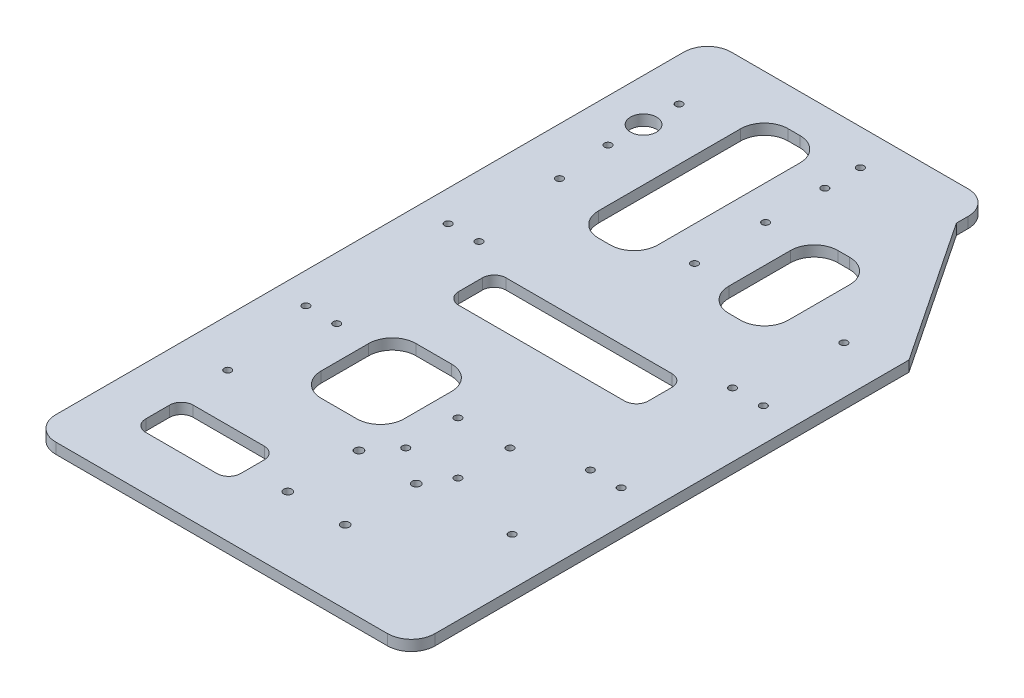
SolidWorks part; units mm, degrees
ref_plane "前视基准面" through (0, 0, 0) normal (0, 0, 1) x (1, 0, 0)
ref_plane "上视基准面" through (0, 0, 0) normal (0, 1, 0) x (1, 0, 0)
ref_plane "右视基准面" through (0, 0, 0) normal (1, 0, 0) x (0, 0, -1)
other "Configuration Table"
sketch "草图1" plane through (0, 0, 0) normal (0, 1, 0) x (1, 0, 0)
  line L1 (-80, 0) -> (80, 0)
  line L6 (0, 0) -> (0, 132.0858) construction
  line L26 (-80, 285) -> (-80, 0)
  line L27 (40, 270) -> (80, 210)
  line L28 (80, 0) -> (80, 210)
  line L29 (-80, 285) -> (40, 285)
  line L30 (40, 285) -> (40, 270)
  point P1 (0, 0)
  dimension "D1" = 160
  dimension "D2" = 285
  dimension "D3" = 120
extrude "凸台-拉伸1" add sketch "草图1" along normal blind 4.5
sketch "草图2" plane through (0, 4.5, 0) normal (0, 1, 0) x (1, 0, 0)
  line L0 (-80, 285) -> (-80, 0) construction
  line L2 (40, 285) -> (-80, 285) construction
  circle A0 centre (-60, 230) radius 6
  dimension "D2" = 12
  dimension "D1" = 20
  dimension "D3" = 55
sketch "草图3" plane through (0, 4.5, 0) normal (0, 1, 0) x (1, 0, 0)
  circle A0 centre (-2.95, 60.8584) radius 1.75
  circle A1 centre (21.25, 60.8584) radius 1.75
  circle A2 centre (21.25, 30.8584) radius 1.75
  circle A3 centre (-2.95, 30.8584) radius 1.75
extrude "切除-拉伸2" cut sketch "草图3" against normal through all
sketch "草图4" plane through (0, 4.5, 0) normal (0, 1, 0) x (1, 0, 0)
  circle A0 centre (-60, 202.5482) radius 1.5
  circle A1 centre (-67, 162.5482) radius 1.5
  circle A2 centre (-54, 162.5482) radius 1.5
  circle A3 centre (-67, 102.5482) radius 1.5
  circle A4 centre (-54, 102.5482) radius 1.5
  circle A5 centre (-60, 62.5482) radius 1.5
  circle A6 centre (60, 62.5482) radius 1.5
  circle A7 centre (53, 102.5482) radius 1.5
  circle A8 centre (66, 102.5482) radius 1.5
  circle A9 centre (53, 162.5482) radius 1.5
  circle A10 centre (66, 162.5482) radius 1.5
  circle A11 centre (60, 202.5482) radius 1.5
  dimension "D1" = 3
  dimension "D2" = 3
extrude "切除-拉伸3" cut sketch "草图4" against normal through all
sketch "草图6" plane through (0, 4.5, 0) normal (0, 1, 0) x (1, 0, 0)
  circle A0 centre (-62, 255) radius 1.5
fillet "圆角1" radius 10 4 edges at (-80, 2.25, -285) (40, 2.25, -285) (80, 2.25, 0) (-80, 2.25, 0)
sketch "草图7" plane through (0, 4.5, 0) normal (0, 1, 0) x (1, 0, 0)
  circle A0 centre (-62, 255) radius 1.5
  circle A1 centre (-62, 225) radius 1.5
extrude "切除-拉伸4" cut sketch "草图7" against normal through all
sketch "草图8" plane through (0, 4.5, 0) normal (0, 1, 0) x (1, 0, 0)
  circle A0 centre (-0.5, 270) radius 1.5
  circle A1 centre (-0.5, 255) radius 1.5
  circle A2 centre (-0.5, 230) radius 1.5
  circle A3 centre (-0.5, 200) radius 1.5
  dimension "D1" = 3
extrude "切除-拉伸5" cut sketch "草图8" against normal through all
sketch "草图9" plane through (0, 4.5, 0) normal (0, 1, 0) x (1, 0, 0)
  line L6 (-80, 275) -> (-80, 10) construction
  line L11 (-30, 269) -> (-25, 269)
  line L14 (-40, 259) -> (-40, 199)
  line L15 (-30, 189) -> (-25, 189)
  line L16 (-15, 259) -> (-15, 199)
  line L17 (30, 285) -> (-70, 285) construction
  line L18 (-70, 0) -> (70, 0) construction
  line L19 (25, 189) -> (30, 189)
  line L20 (15, 199) -> (15, 225)
  line L21 (25, 235) -> (30, 235)
  line L22 (40, 199) -> (40, 225)
  line L23 (-35, 155) -> (35, 155)
  line L24 (-40, 150) -> (-40, 140)
  line L25 (-35, 135) -> (35, 135)
  line L26 (40, 150) -> (40, 140)
  line L27 (-30, 112) -> (-15, 112)
  line L28 (-40, 102) -> (-40, 82)
  line L29 (-30, 72) -> (-15, 72)
  line L31 (-54.5, 22.5) -> (-24.5, 22.5)
  line L32 (-59.5, 27.5) -> (-59.5, 37.5)
  line L33 (-54.5, 42.5) -> (-24.5, 42.5)
  line L34 (-19.5, 27.5) -> (-19.5, 37.5)
  line L35 (-5, 102) -> (-5, 82)
  arc A4 (-40, 82) -> (-30, 72) centre (-30, 82) ccw
  arc A5 (-15, 72) -> (-5, 82) centre (-15, 82) ccw
  arc A6 (-5, 102) -> (-15, 112) centre (-15, 102) ccw
  arc A7 (-40, 102) -> (-30, 112) centre (-30, 102) cw
  arc A8 (40, 225) -> (30, 235) centre (30, 225) ccw
  arc A9 (30, 189) -> (40, 199) centre (30, 199) ccw
  arc A10 (25, 189) -> (15, 199) centre (25, 199) cw
  arc A11 (15, 225) -> (25, 235) centre (25, 225) cw
  arc A12 (-15, 259) -> (-25, 269) centre (-25, 259) ccw
  arc A13 (-25, 189) -> (-15, 199) centre (-25, 199) ccw
  arc A14 (-30, 189) -> (-40, 199) centre (-30, 199) cw
  arc A15 (-40, 259) -> (-30, 269) centre (-30, 259) cw
  arc A16 (-19.5, 27.5) -> (-24.5, 22.5) centre (-24.5, 27.5) cw
  arc A17 (-19.5, 37.5) -> (-24.5, 42.5) centre (-24.5, 37.5) ccw
  arc A18 (-59.5, 27.5) -> (-54.5, 22.5) centre (-54.5, 27.5) ccw
  arc A19 (-59.5, 37.5) -> (-54.5, 42.5) centre (-54.5, 37.5) cw
  arc A20 (40, 140) -> (35, 135) centre (35, 140) cw
  arc A21 (40, 150) -> (35, 155) centre (35, 150) ccw
  arc A22 (-40, 140) -> (-35, 135) centre (-35, 140) ccw
  arc A23 (-40, 150) -> (-35, 155) centre (-35, 150) cw
  point P44 (-40, 72)
  point P47 (-5, 72)
  point P52 (-40, 112)
  point P57 (40, 189)
  point P60 (15, 189)
  point P63 (15, 235)
  point P66 (-15, 269)
  point P69 (-15, 189)
  point P74 (-40, 269)
  point P79 (-19.5, 42.5)
  point P82 (-59.5, 22.5)
  point P85 (-59.5, 42.5)
  point P90 (40, 155)
  point P93 (-40, 135)
  point P96 (-40, 155)
  dimension "D2" = 25
  dimension "D6" = 46
  dimension "D24" = 5
  dimension "D16" = 20
  dimension "D1" = 40
  dimension "D3" = 80
  dimension "D4" = 16
  dimension "D5" = 25
  dimension "D7" = 30
  dimension "D8" = 50
  dimension "D9" = 80
  dimension "D10" = 20
  dimension "D11" = 40
  dimension "D12" = 135
  dimension "D13" = 15
  dimension "D14" = 40
  dimension "D15" = 72
  dimension "D18" = 35
  dimension "D19" = 40
  dimension "D20" = 20
  dimension "D21" = 20.5
  dimension "D22" = 22.5
extrude "切除-拉伸6" cut sketch "草图9" against normal through all
sketch "草图10" plane through (0, 4.5, 0) normal (0, 1, 0) x (1, 0, 0)
  circle A0 centre (-62, 240) radius 5.5
  dimension "D1" = 11
extrude "切除-拉伸7" cut sketch "草图10" against normal through all
sketch "草图11" plane through (0, 4.5, 0) normal (0, 1, 0) x (1, 0, 0)
  circle A0 centre (6, 93.669) radius 1.5
  circle A1 centre (28, 93.669) radius 1.5
  circle A2 centre (6, 71.669) radius 1.5
  circle A3 centre (28, 71.669) radius 1.5
  dimension "D1" = 3
  dimension "D2" = 3
  dimension "D3" = 3
  dimension "D4" = 3
extrude "切除-拉伸8" cut sketch "草图11" against normal through all
